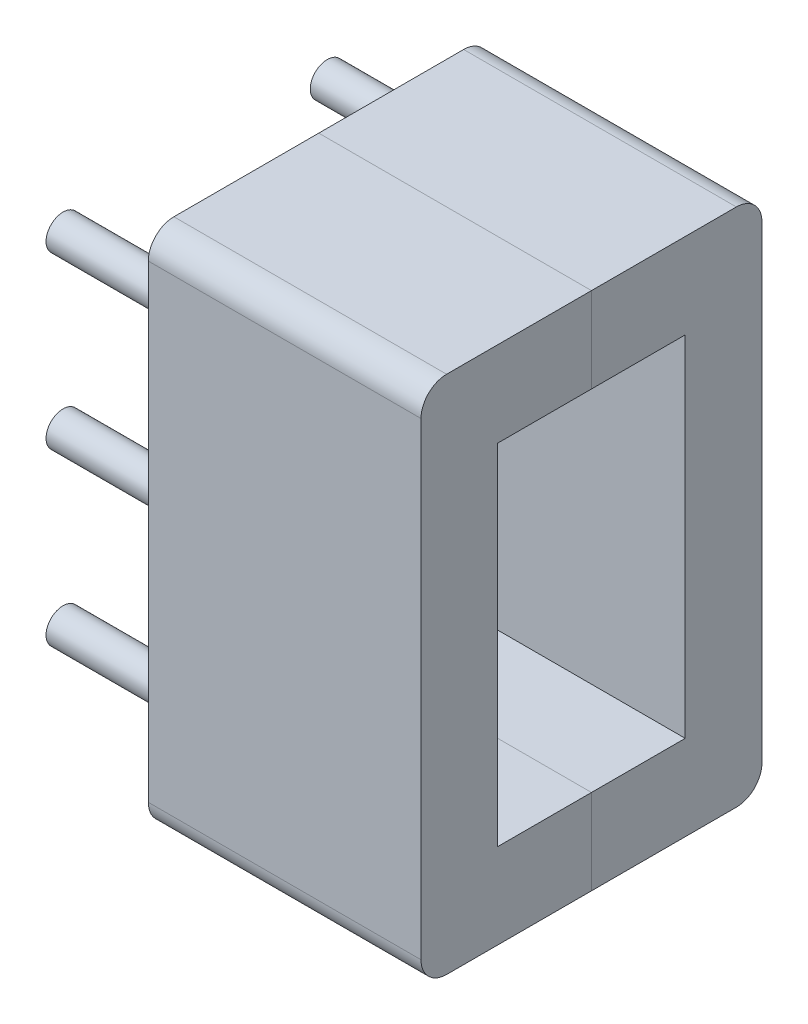
SolidWorks part; units mm, degrees
ref_plane "Alzado" through (0, 0, 0) normal (0, 0, 1) x (1, 0, 0)
ref_plane "Planta" through (0, 0, 0) normal (0, 1, 0) x (1, 0, 0)
ref_plane "Vista lateral" through (0, 0, 0) normal (1, 0, 0) x (0, 0, -1)
sketch "Croquis2" plane through (0, 0, 0) normal (1, 0, 0) x (0, 0, -1)
  line L0 (0, 24.489) -> (0, -53.3578) construction
  line L1 (5.835, 13.2874) -> (5.835, 12.9749) construction
  line L2 (10, 6.2874) -> (10, 3.7874) construction
  line L3 (5.835, -38.7126) -> (5.835, -38.4002) construction
  line L4 (5.835, -38.7126) -> (8, -38.7126) construction
  line L5 (9, -32.7126) -> (9, -37.7126) construction
  line L6 (10, -29.2126) -> (10, -31.7126) construction
  line L7 (5.835, 13.2874) -> (8, 13.2874) construction
  line L8 (9, 7.2874) -> (9, 12.2874) construction
  line L9 (6.5, 7.2874) -> (-6.5, 7.2874) construction
  line L10 (10, -29.2126) -> (10, 3.7874) construction
  line L11 (5.835, 13.2874) -> (5.835, 12.9749) construction
  line L12 (10, 6.2874) -> (10, 3.7874) construction
  line L13 (5.835, -38.7126) -> (5.835, -38.4002) construction
  line L14 (5.835, -38.7126) -> (8, -38.7126) construction
  line L15 (9, -32.7126) -> (9, -37.7126) construction
  line L16 (10, -29.2126) -> (10, -31.7126) construction
  line L17 (5.835, 13.2874) -> (8, 13.2874) construction
  line L18 (9, 7.2874) -> (9, 12.2874) construction
  line L19 (6.5, 7.2874) -> (-6.5, 7.2874) construction
  line L20 (10, -29.2126) -> (10, 3.7874) construction
  line L21 (-20, 17.7874) -> (20, 17.7874)
  line L22 (20, 17.7874) -> (20, -43.2126)
  line L24 (20, -43.2126) -> (-20, -43.2126)
  line L25 (-20, 17.7874) -> (-20, -43.2126)
  line L26 (-6.5, -32.7126) -> (6.5, -32.7126) construction
  line L27 (9, -32.7126) -> (6.5, -32.7126) construction
  line L28 (-6.5, -32.7126) -> (6.5, -32.7126) construction
  line L29 (9, -32.7126) -> (6.5, -32.7126) construction
  line L30 (-3, -33.7126) -> (-3, -32.7126) construction
  line L31 (3, -33.7126) -> (3, -32.7126) construction
  line L32 (-3, -33.7126) -> (-3, -32.7126) construction
  line L33 (3, -33.7126) -> (3, -32.7126) construction
  arc A0 (5.835, -38.4002) -> (4.335, -38.4002) centre (5.085, -36.3426) ccw construction
  arc A1 (4.335, 12.9749) -> (5.835, 12.9749) centre (5.085, 10.9174) ccw construction
  arc A2 (5.835, -38.4002) -> (4.335, -38.4002) centre (5.085, -36.3426) ccw construction
  arc A3 (4.335, 12.9749) -> (5.835, 12.9749) centre (5.085, 10.9174) ccw construction
  arc A4 (8, -38.7126) -> (9, -37.7126) centre (8, -37.7126) ccw construction
  arc A5 (9, -32.7126) -> (10, -31.7126) centre (9, -31.7126) ccw construction
  arc A6 (9, 12.2874) -> (8, 13.2874) centre (8, 12.2874) ccw construction
  arc A7 (10, 6.2874) -> (9, 7.2874) centre (9, 6.2874) ccw construction
  arc A8 (8, -38.7126) -> (9, -37.7126) centre (8, -37.7126) ccw construction
  arc A9 (9, -32.7126) -> (10, -31.7126) centre (9, -31.7126) ccw construction
  arc A10 (9, 12.2874) -> (8, 13.2874) centre (8, 12.2874) ccw construction
  arc A11 (10, 6.2874) -> (9, 7.2874) centre (9, 6.2874) ccw construction
  point P31 (0, -43.2126)
  point P33 (0, 17.7874)
  dimension "D1" = 4.5
  dimension "D2" = 10
  dimension "D3" = 4.5
extrude "Saliente-Extruir1" add sketch "Croquis2" against normal blind 32
sketch "Croquis4" plane through (0, 0, 0) normal (1, 0, 0) x (0, 0, -1)
  line L0 (3, -33.7126) -> (3, -32.7126) construction
  line L1 (-6.5, -32.7126) -> (6.5, -32.7126) construction
  line L2 (9, -32.7126) -> (6.5, -32.7126) construction
  line L3 (10, -29.2126) -> (10, -31.7126) construction
  line L4 (10, 6.2874) -> (10, 3.7874) construction
  line L5 (10, -29.2126) -> (10, 3.7874) construction
  line L6 (6.5, 7.2874) -> (-6.5, 7.2874) construction
  line L7 (0, 24.489) -> (0, -53.3578) construction
  line L8 (3, -33.7126) -> (3, -32.7126) construction
  line L9 (-6.5, -32.7126) -> (6.5, -32.7126) construction
  line L10 (9, -32.7126) -> (6.5, -32.7126) construction
  line L11 (10, -29.2126) -> (10, -31.7126) construction
  line L12 (10, 6.2874) -> (10, 3.7874) construction
  line L13 (10, -29.2126) -> (10, 3.7874) construction
  line L14 (6.5, 7.2874) -> (-6.5, 7.2874) construction
  line L15 (0, 24.489) -> (0, -53.3578) construction
  line L16 (-11, 7.7874) -> (11, 7.7874)
  line L17 (11, 7.7874) -> (11, -33.2126)
  line L19 (-11, 7.7874) -> (-11, -33.2126)
  line L35 (3, -33.7126) -> (2.5, -34.2126) construction
  line L43 (11, -33.2126) -> (-11, -33.2126)
  arc A0 (9, -32.7126) -> (10, -31.7126) centre (9, -31.7126) ccw construction
  arc A1 (9, -32.7126) -> (10, -31.7126) centre (9, -31.7126) ccw construction
  point P14 (0, -33.2126)
  point P20 (0, 7.7874)
  point P22 (0, -43.2126)
  dimension "D1" = 0.5
  dimension "D2" = 1
  dimension "D3" = 0.5
  dimension "D8" = 0.5
  dimension "D9" = 2.5
extrude "Cortar-Extruir1" cut sketch "Croquis4" against normal through all both and the other way through all
sketch "Croquis5" plane through (-32, 0, 0) normal (-1, 0, 0) x (0, 0, 1)
  line L0 (-9, 7.2874) -> (-9, 12.2874) construction
  line L1 (-9, -32.7126) -> (-9, -37.7126) construction
  line L2 (-5.835, -38.7126) -> (-8, -38.7126) construction
  line L3 (-5.835, 13.2874) -> (-8, 13.2874) construction
  line L4 (-9, 7.2874) -> (-9, 12.2874) construction
  line L5 (-9, -32.7126) -> (-9, -37.7126) construction
  line L6 (-5.835, -38.7126) -> (-8, -38.7126) construction
  line L7 (-5.835, 13.2874) -> (-8, 13.2874) construction
  line L8 (0, 24.489) -> (0, -53.3578) construction
  line L9 (0, 24.489) -> (0, -53.3578) construction
  line L10 (9.5, 13.7874) -> (-9.5, 13.7874)
  line L11 (-9.5, 13.7874) -> (-9.5, -39.2126)
  line L12 (-9.5, -39.2126) -> (9.5, -39.2126)
  line L13 (9.5, 13.7874) -> (9.5, -39.2126)
  arc A0 (-4.335, -38.4002) -> (-5.835, -38.4002) centre (-5.085, -36.3426) ccw construction
  arc A1 (-5.835, 12.9749) -> (-4.335, 12.9749) centre (-5.085, 10.9174) ccw construction
  arc A2 (-4.335, -38.4002) -> (-5.835, -38.4002) centre (-5.085, -36.3426) ccw construction
  arc A3 (-5.835, 12.9749) -> (-4.335, 12.9749) centre (-5.085, 10.9174) ccw construction
  point P21 (0, -39.2126)
  point P22 (0, 13.7874)
  dimension "D1" = 0.5
  dimension "D2" = 0.5
  dimension "D3" = 0.5
extrude "Cortar-Extruir2" cut sketch "Croquis5" against normal blind 8 and the other way through all
sketch "Croquis7" plane through (-24, 0, 0) normal (-1, 0, 0) x (0, 0, 1)
  line L4 (-9.5, 7.7874) -> (9.5, 7.7874)
  line L5 (9.5, 7.7874) -> (9.5, 13.7874)
  line L6 (9.5, 13.7874) -> (-9.5, 13.7874)
  line L7 (-9.5, 13.7874) -> (-9.5, 7.7874)
  line L8 (-9.5, 7.7874) -> (9.5, 7.7874)
  line L9 (9.5, 7.7874) -> (9.5, 13.7874)
  line L10 (9.5, 13.7874) -> (-9.5, 13.7874)
  line L11 (-9.5, 13.7874) -> (-9.5, 7.7874)
  line L12 (9.5, -33.2126) -> (-9.5, -33.2126)
  line L13 (-9.5, -33.2126) -> (-9.5, -39.2126)
  line L14 (-9.5, -39.2126) -> (9.5, -39.2126)
  line L15 (9.5, -39.2126) -> (9.5, -33.2126)
  line L16 (9.5, -33.2126) -> (-9.5, -33.2126)
  line L17 (-9.5, -33.2126) -> (-9.5, -39.2126)
  line L18 (-9.5, -39.2126) -> (9.5, -39.2126)
  line L19 (9.5, -39.2126) -> (9.5, -33.2126)
  dimension "D1" = 0
  dimension "D2" = 0
extrude "Saliente-Extruir2" add sketch "Croquis7" along normal up to surface (5.5 mm away) from offset 2.5 up to face at (-32, -12.7126, 0)
sketch "Croquis9" plane through (-32, 0, 0) normal (1, 0, 0) x (0, 0, -1)
  line L0 (-15.5, 3.7699) -> (-15.5, -40.0796) construction
  line L2 (100, 3.7699) -> (-100, 3.7699) construction
  line L3 (100, 12.7699) -> (-100, 12.7699) construction
  line L4 (-20, 17.7874) -> (-20, -43.2126) construction
  line L5 (-11, -33.2126) -> (-11, 7.7874) construction
  line L6 (-20, 17.7874) -> (-20, -43.2126) construction
  line L7 (-11, -33.2126) -> (-11, 7.7874) construction
  line L8 (0, 24.489) -> (0, -53.3578) construction
  line L9 (0, 24.489) -> (0, -53.3578) construction
  line L10 (-20, 6.2236) -> (-11, 6.2236) construction
  line L11 (-15.5, 3.7699) -> (-15.5, 12.7699) construction
  circle A0 centre (-15.5, 8.2699) radius 2
  circle A1 centre (-15.5, -31.7301) radius 2
  circle A2 centre (-15.5, -11.7301) radius 2
  circle A3 centre (15.5, -31.7301) radius 2
  circle A4 centre (15.5, -11.7301) radius 2
  circle A5 centre (15.5, 8.2699) radius 2
  point P14 (-15.5, 6.2236)
  dimension "D1" = 40
  dimension "D2" = 20
  dimension "D3" = 4
extrude "Saliente-Extruir3" add sketch "Croquis9" against normal blind 14.5
fillet "Redondeo1" radius 3 4 edges at (-16, -43.2126, 20) (-16, -43.2126, -20) (-16, 17.7874, -20) (-16, 17.7874, 20)
sketch "Croquis10" plane through (0, 0, 20) normal (0, 0, 1) x (1, 0, 0)
  line L0 (0, 14.7874) -> (-32, 14.7874) construction
  line L1 (0, 14.7874) -> (-32, 14.7874) construction
split "Partir1" trim tools "Alzado" bodies to split 108 resulting bodies 106 107
